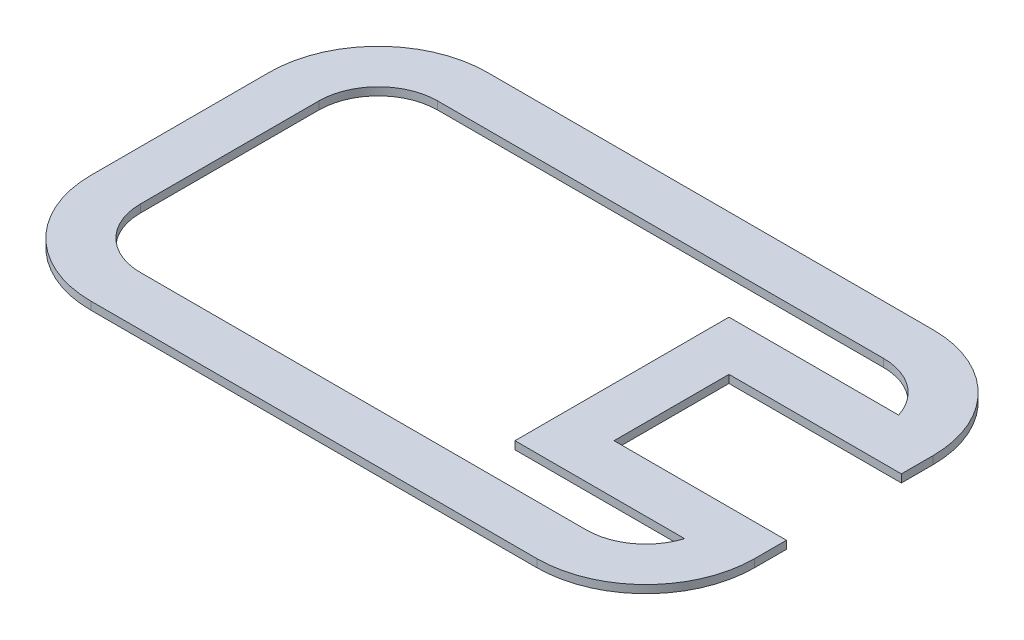
SolidWorks part; units mm, degrees
ref_plane "Front Plane" through (0, 0, 0) normal (0, 0, 1) x (1, 0, 0)
ref_plane "Top Plane" through (0, 0, 0) normal (0, 1, 0) x (1, 0, 0)
ref_plane "Right Plane" through (0, 0, 0) normal (1, 0, 0) x (0, 0, -1)
sketch "Sketch1" plane through (0, 0, 0) normal (0, 1, 0) x (1, 0, 0)
  line L0 (55, 25) -> (280, 25)
  line L1 (55, 0) -> (280, 0)
  line L2 (0, 55) -> (0, 145)
  line L3 (55, 200) -> (280, 200)
  line L4 (335, 145) -> (335, 129)
  line L5 (335, 55) -> (335, 71)
  line L6 (308.6182, 46) -> (308.6182, 46)
  line L7 (223, 46) -> (308.6182, 46)
  line L8 (335, 129) -> (248, 129)
  line L9 (223, 154) -> (223, 46)
  line L10 (308.6182, 154) -> (223, 154)
  line L11 (248, 129) -> (248, 71)
  line L12 (248, 71) -> (335, 71)
  line L13 (308.6182, 154) -> (308.6182, 154)
  line L14 (55, 175) -> (280, 175)
  line L15 (25, 55) -> (25, 145)
  arc A0 (55, 0) -> (0, 55) centre (55, 55) cw
  arc A1 (280, 0) -> (335, 55) centre (280, 55) ccw
  arc A2 (280, 200) -> (335, 145) centre (280, 145) cw
  arc A3 (0, 145) -> (55, 200) centre (55, 145) cw
  arc A4 (280, 25) -> (308.6182, 46) centre (280, 55) ccw
  arc A5 (280, 175) -> (308.6182, 154) centre (280, 145) cw
  arc A6 (25, 145) -> (55, 175) centre (55, 145) cw
  arc A7 (55, 25) -> (25, 55) centre (55, 55) cw
  point P7 (0, 0)
  point P15 (0, 200)
  point P28 (0, 0)
  dimension "D3" = 55
  dimension "D7" = 87
  dimension "D1" = 335
  dimension "D2" = 200
  dimension "D5" = 58
  dimension "D4" = 25
extrude "Boss-Extrude1" add sketch "Sketch1" along normal blind 4
